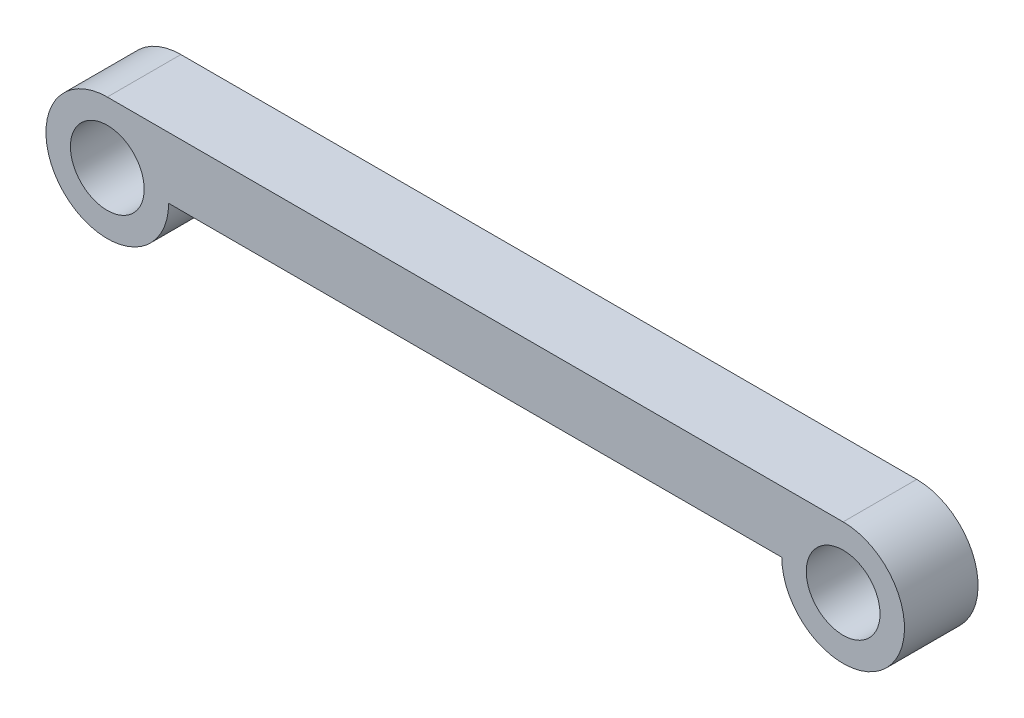
SolidWorks part; units mm, degrees
material "Thornel Mat VMA"
ref_plane "前视基准面" through (0, 0, 0) normal (0, 0, 1) x (1, 0, 0)
ref_plane "上视基准面" through (0, 0, 0) normal (0, 1, 0) x (1, 0, 0)
ref_plane "右视基准面" through (0, 0, 0) normal (1, 0, 0) x (0, 0, -1)
other "Configuration Table"
sketch "草图1" plane through (0, 0, 0) normal (0, 0, 1) x (1, 0, 0)
  line L0 (0, 0) -> (15.0023, 0)
  line L1 (55, 0) -> (-55, 0) construction
  line L2 (-12.4974, -2.5008) -> (12.5015, -2.5008)
  line L5 (0, 0) -> (-14.9982, 0)
  arc A2 (-14.9982, 0) -> (-12.4974, -2.5008) centre (-14.9982, -2.5008) ccw
  arc A3 (15.0023, 0) -> (12.5015, -2.5008) centre (15.0023, -2.5008) cw
  circle A4 centre (-14.9982, -2.5008) radius 1.5037
  circle A5 centre (15.0023, -2.5008) radius 1.504
extrude "凸台-拉伸1" add sketch "草图1" along normal blind 3
